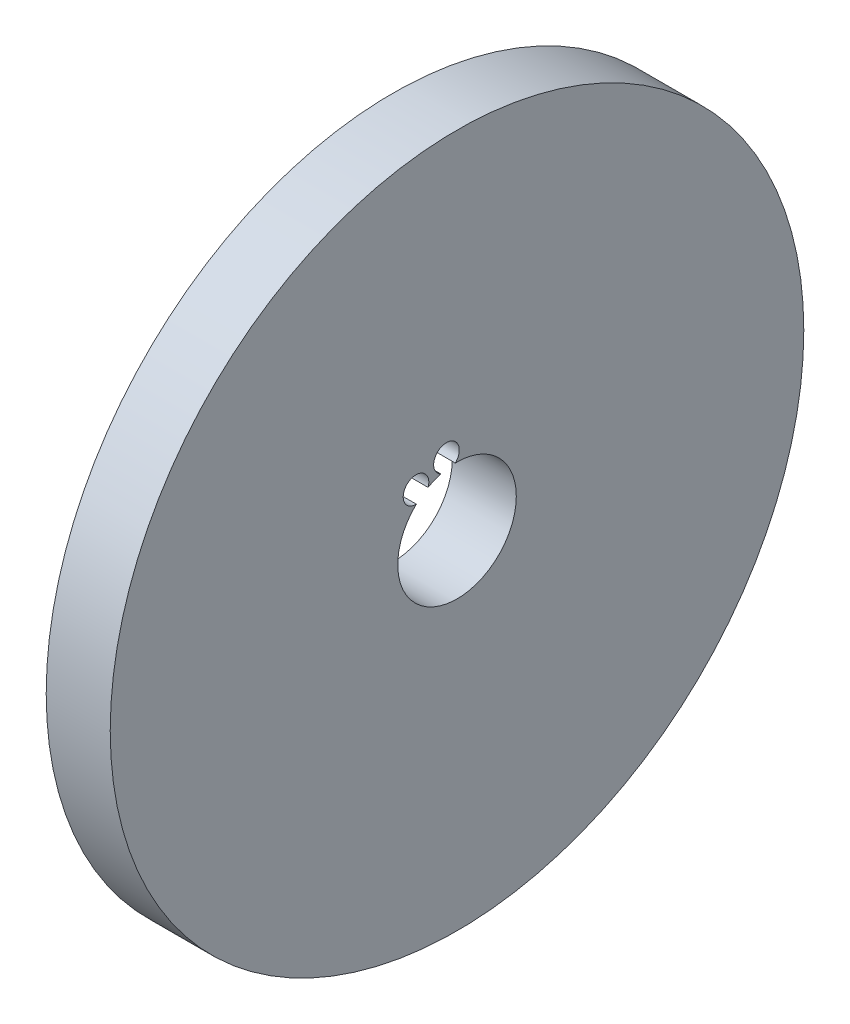
SolidWorks part; units mm, degrees
ref_plane "Front Plane" through (0, 0, 0) normal (0, 0, 1) x (1, 0, 0)
ref_plane "Top Plane" through (0, 0, 0) normal (0, 1, 0) x (1, 0, 0)
ref_plane "Right Plane" through (0, 0, 0) normal (1, 0, 0) x (0, 0, -1)
sketch "Axial profile (mm)" plane through (0, 0, 0) normal (0, 0, 1) x (1, 0, 0)
  line L0 (-110, 0) -> (75, 0) construction
  line L1 (13.7, 11.1125) -> (25.7, 11.1125)
  line L2 (25.7, 11.1125) -> (25.7, 65)
  line L3 (25.7, 65) -> (13.7, 65)
  line L4 (13.7, 65) -> (13.7, 11.1125)
revolve "Full revolution" add sketch "Axial profile (mm)" angle 360 about L0
sketch "Sketch2" plane through (0, 0, 0) normal (1, 0, 0) x (0, 0, -1)
  circle A0 centre (-1.9774, 12.8487) radius 2.4
  circle A1 centre (-7.6872, 10.4836) radius 2.4
extrude "Axial holes" cut sketch "Sketch2" against normal through all and the other way through all
